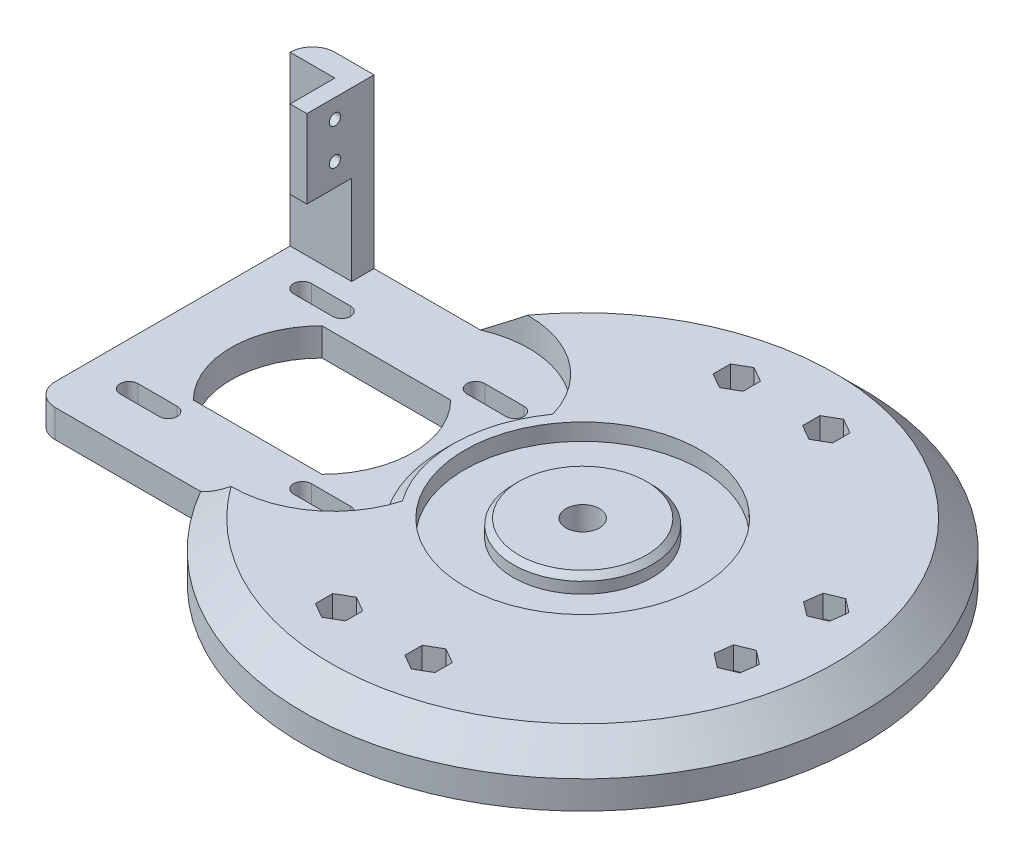
SolidWorks part; units mm, degrees
ref_plane "Front Plane" through (0, 0, 0) normal (0, 0, 1) x (1, 0, 0)
ref_plane "Top Plane" through (0, 0, 0) normal (0, 1, 0) x (1, 0, 0)
ref_plane "Right Plane" through (0, 0, 0) normal (1, 0, 0) x (0, 0, -1)
sketch "Sketch1" plane through (0, 0, 0) normal (0, 1, 0) x (1, 0, 0)
  line L0 (-43.3013, 25) -> (-73.3013, 25)
  line L2 (-73.3013, 25) -> (-73.3013, -25)
  line L3 (-43.3013, -25) -> (-73.3013, -25)
  line L4 (-50, 0) -> (-73.3013, -25) construction
  line L5 (-73.3013, 25) -> (-50, 0) construction
  line L6 (0, 0) -> (-50, 0) construction
  line L7 (-50, 0) -> (-73.3013, 0) construction
  circle A0 centre (0, 0) radius 50
  point P4 (-50, 0)
  dimension "D1" = 100
  dimension "D2" = 50
  dimension "D3" = 30
extrude "Boss-Extrude1" add sketch "Sketch1" along normal blind 5 contours A0 L0 L2 L3 | A0
sketch "Sketch2" plane through (0, 5, 0) normal (0, 1, 0) x (1, 0, 0)
  circle A0 centre (0, 0) radius 12.4
  circle A1 centre (0, 0) radius 9.4
  circle A2 centre (0, 0) radius 21.1
  circle A3 centre (0, 0) radius 25.1
  dimension "D1" = 24.8
  dimension "D2" = 3
  dimension "D3" = 42.2
  dimension "D4" = 4
extrude "Boss-Extrude2" add sketch "Sketch2" along normal blind 5 contours A3 A2 | A0 A1
chamfer "Chamfer1" distance 1 angle 45 1 edges at (0, 10, 12.4)
sketch "Sketch3" plane through (0, 5, 0) normal (0, 1, 0) x (1, 0, 0)
  circle A0 centre (0, 0) radius 9.4
extrude "Cut-Extrude1" cut sketch "Sketch3" against normal blind 5
sketch "Sketch4" plane through (0, 5, 0) normal (0, 1, 0) x (1, 0, 0)
  line L0 (-31.1, 0) -> (-62.1, 0) construction
  line L2 (-65.6, 15.5) -> (-58.6, 15.5) construction
  line L3 (-65.6, 17.1) -> (-58.6, 17.1)
  line L4 (-65.6, 13.9) -> (-58.6, 13.9)
  line L5 (-34.6, 15.5) -> (-27.6, 15.5) construction
  line L6 (-34.6, 17.1) -> (-27.6, 17.1)
  line L7 (-34.6, 13.9) -> (-27.6, 13.9)
  line L8 (-43.3013, 25) -> (-73.3013, 25) construction
  line L9 (-34.6, -15.5) -> (-27.6, -15.5) construction
  line L10 (-34.6, -17.1) -> (-27.6, -17.1)
  line L11 (-34.6, -13.9) -> (-27.6, -13.9)
  line L12 (-65.6, -15.5) -> (-58.6, -15.5) construction
  line L13 (-65.6, -17.1) -> (-58.6, -17.1)
  line L14 (-65.6, -13.9) -> (-58.6, -13.9)
  line L15 (-31.1, 15.5) -> (-31.1, -15.5) construction
  line L16 (-31.1, -15.5) -> (-62.1, -15.5) construction
  line L17 (-62.1, -15.5) -> (-62.1, 15.5) construction
  line L18 (-62.1, 15.5) -> (-31.1, 15.5) construction
  line L19 (-25.1, 0) -> (-31.1, 0) construction
  line L20 (-58.1, 11.5) -> (-35.1, 11.5)
  line L21 (-58.1, -11.5) -> (-35.1, -11.5)
  arc A2 (-65.6, 17.1) -> (-65.6, 13.9) centre (-65.6, 15.5) ccw
  arc A3 (-58.6, 13.9) -> (-58.6, 17.1) centre (-58.6, 15.5) ccw
  arc A4 (-34.6, 17.1) -> (-34.6, 13.9) centre (-34.6, 15.5) ccw
  arc A5 (-27.6, 13.9) -> (-27.6, 17.1) centre (-27.6, 15.5) ccw
  arc A6 (-34.6, -17.1) -> (-34.6, -13.9) centre (-34.6, -15.5) cw
  arc A7 (-27.6, -13.9) -> (-27.6, -17.1) centre (-27.6, -15.5) cw
  arc A8 (-65.6, -17.1) -> (-65.6, -13.9) centre (-65.6, -15.5) cw
  arc A9 (-58.6, -13.9) -> (-58.6, -17.1) centre (-58.6, -15.5) cw
  circle A10 centre (0, 0) radius 25.1 construction
  circle A11 centre (0, 0) radius 25.1 construction
  arc A13 (-58.1, 11.5) -> (-58.1, -11.5) centre (-46.6, 0) ccw
  arc A14 (-35.1, 11.5) -> (-35.1, -11.5) centre (-46.6, 0) cw
  point P10 (-62.1, 15.5)
  point P17 (-31.1, 15.5)
  point P26 (-31.1, -15.5)
  point P33 (-62.1, -15.5)
  point P46 (-46.6, 11.5)
  dimension "D3" = 4
  dimension "D1" = 7
  dimension "D2" = 3.2
  dimension "15.5" = 15.5
  dimension "D4" = 31
  dimension "D5" = 6
extrude "Cut-Extrude2" cut sketch "Sketch4" against normal blind 5
sketch "Sketch5" plane through (0, 5, 0) normal (0, 1, 0) x (1, 0, 0)
  line L1 (0, 0) -> (-6.0888, 0) construction
  circle A0 centre (0, 0) radius 25.1 construction
  arc A1 (-43.3013, -25) -> (-43.3013, 25) centre (0, 0) ccw
  arc A2 (-19.5937, -15.6875) -> (-19.5937, 15.6875) centre (0, 0) ccw
  arc A3 (-43.3013, -25) -> (-19.5937, -15.6875) centre (-36.1037, -8.49) ccw
  arc A4 (-43.3013, 25) -> (-19.5937, 15.6875) centre (-36.1037, 8.49) cw
extrude "Boss-Extrude3" add sketch "Sketch5" along normal blind 5
sketch "Sketch6" plane through (0, 10, 0) normal (0, 1, 0) x (1, 0, 0)
  line L0 (0, 0) -> (8.3145, 0) construction
  line L1 (0, -21.1) -> (0, -50) construction
  line L2 (-8, -35.55) -> (8, -35.55) construction
  line L3 (21.1, 0) -> (50, 0) construction
  line L4 (35.55, 8) -> (35.55, -8) construction
  circle A0 centre (0, 0) radius 21.1 construction
  circle A1 centre (0, 0) radius 21.1 construction
  arc A2 (-43.3013, -25) -> (-43.3013, 25) centre (0, 0) ccw construction
  circle A3 centre (8, -35.55) radius 1.5
  circle A4 centre (-8, -35.55) radius 1.5
  circle A5 centre (8, 35.55) radius 1.5
  circle A6 centre (-8, 35.55) radius 1.5
  circle A7 centre (35.55, -8) radius 1.5
  circle A8 centre (35.55, 8) radius 1.5
  point P28 (0, -35.55)
  point P33 (35.55, 0)
  dimension "D1" = 3
  dimension "D2" = 8
  dimension "D3" = 16
extrude "Cut-Extrude3" cut sketch "Sketch6" against normal blind 10
sketch "Sketch7" plane through (0, 10, 0) normal (0, 1, 0) x (1, 0, 0)
  line L0 (0, 0) -> (5.3153, 0) construction
  line L1 (-8, -38.65) -> (-5.3153, -37.1)
  line L2 (-5.3153, -37.1) -> (-5.3153, -34)
  line L3 (-5.3153, -34) -> (-8, -32.45)
  line L4 (-8, -32.45) -> (-10.6847, -34)
  line L5 (-10.6847, -34) -> (-10.6847, -37.1)
  line L6 (-10.6847, -37.1) -> (-8, -38.65)
  line L7 (8, -38.65) -> (10.6847, -37.1)
  line L8 (10.6847, -37.1) -> (10.6847, -34)
  line L9 (10.6847, -34) -> (8, -32.45)
  line L10 (8, -32.45) -> (5.3153, -34)
  line L11 (5.3153, -34) -> (5.3153, -37.1)
  line L12 (5.3153, -37.1) -> (8, -38.65)
  line L13 (5.3153, 37.1) -> (8, 38.65)
  line L14 (5.3153, 34) -> (5.3153, 37.1)
  line L15 (8, 32.45) -> (5.3153, 34)
  line L16 (10.6847, 34) -> (8, 32.45)
  line L17 (10.6847, 37.1) -> (10.6847, 34)
  line L18 (8, 38.65) -> (10.6847, 37.1)
  line L19 (-10.6847, 37.1) -> (-8, 38.65)
  line L20 (-10.6847, 34) -> (-10.6847, 37.1)
  line L21 (-8, 32.45) -> (-10.6847, 34)
  line L22 (-5.3153, 34) -> (-8, 32.45)
  line L23 (-5.3153, 37.1) -> (-5.3153, 34)
  line L24 (-8, 38.65) -> (-5.3153, 37.1)
  line L26 (32.6851, 6.8158) -> (35.1431, 4.9268)
  line L27 (35.1431, 4.9268) -> (38.008, 6.111)
  line L28 (38.008, 6.111) -> (38.4149, 9.1842)
  line L29 (38.4149, 9.1842) -> (35.9569, 11.0732)
  line L30 (35.9569, 11.0732) -> (33.092, 9.889)
  line L31 (33.092, 9.889) -> (32.6851, 6.8158)
  line L32 (32.6837, -9.1807) -> (35.1393, -11.0727)
  line L33 (35.1393, -11.0727) -> (38.0057, -9.892)
  line L34 (38.0057, -9.892) -> (38.4163, -6.8193)
  line L35 (38.4163, -6.8193) -> (35.9607, -4.9273)
  line L36 (35.9607, -4.9273) -> (33.0943, -6.108)
  line L37 (33.0943, -6.108) -> (32.6837, -9.1807)
  circle A0 centre (-8, -35.55) radius 2.6847 construction
  circle A1 centre (8, -35.55) radius 2.6847 construction
  circle A2 centre (35.55, 8) radius 2.6847 construction
  circle A3 centre (35.55, -8) radius 2.6847 construction
  dimension "D1" = 6.2
  dimension "D2" = 6.2
  dimension "D3" = 6.2
extrude "Cut-Extrude4" cut sketch "Sketch7" against normal blind 4
chamfer "Chamfer4" distance 2 angle 45 1 edges at (-25.1, 10, 0)
sketch "Sketch8" plane through (0, 5, 0) normal (0, 1, 0) x (1, 0, 0)
  line L0 (-67.2, -15.5) -> (-67.2, 15.5) construction
  line L2 (-26, 15.5) -> (-26, -15.5) construction
  line L3 (-26, 0) -> (-67.2, 0) construction
  line L5 (-46.6, 0) -> (-46.6, 3.8786) construction
  line L6 (-62.1, 11.5) -> (-39.1, 11.5)
  line L8 (-62.1, -11.5) -> (-39.1, -11.5)
  arc A1 (-65.6, -13.9) -> (-65.6, -17.1) centre (-65.6, -15.5) ccw construction
  arc A2 (-65.6, 17.1) -> (-65.6, 13.9) centre (-65.6, 15.5) ccw construction
  arc A3 (-27.6, 13.9) -> (-27.6, 17.1) centre (-27.6, 15.5) ccw construction
  arc A4 (-27.6, -17.1) -> (-27.6, -13.9) centre (-27.6, -15.5) ccw construction
  arc A10 (-62.1, 11.5) -> (-62.1, -11.5) centre (-50.6, 0) ccw
  arc A11 (-39.1, 11.5) -> (-39.1, -11.5) centre (-50.6, 0) cw
  point P22 (-50.6, 11.5)
sketch "Sketch10" plane through (0, 5, 0) normal (0, 1, 0) x (1, 0, 0)
  circle A0 centre (0, 0) radius 21.6386
  circle A1 centre (0, 0) radius 12.4
extrude "Boss-Extrude4" add sketch "Sketch10" along normal blind 2
chamfer "Chamfer5" distance 5 angle 45 1 edges at (50, 10, 0)
sketch "Sketch14" plane through (0, 0, 0) normal (0, -1, 0) x (1, 0, 0)
  circle A0 centre (0, 0) radius 9.4
  circle A1 centre (0, 0) radius 3
  dimension "D1" = 18.8
  dimension "D2" = 6
extrude "Boss-Extrude6" add sketch "Sketch14" along normal up to surface (10 mm away) from surface at -10 up to face at (35.55, 0, 9.5) starting at face at (0, 10, 11.4)
sketch "Sketch16" plane through (0, 0, 0) normal (0, -1, 0) x (1, 0, 0)
  circle A0 centre (0, 0) radius 9.4
  dimension "D1" = 18.8
extrude "Cut-Extrude8" cut sketch "Sketch16" against normal blind 4
fillet "Fillet3" radius 4 2 edges at (-73.3013, 2.5, -25) (-73.3013, 2.5, 25)
sketch "Sketch17" plane through (0, 5, 0) normal (0, 1, 0) x (1, 0, 0)
  line L5 (-73.3013, 21) -> (-73.3013, -21) construction
  line L6 (-73.3013, 0) -> (-64.3362, 0) construction
  line L8 (-65.3013, 25) -> (-65.3013, 21)
  line L9 (-69.3013, 25) -> (-65.3013, 25)
  line L11 (-65.3013, 21) -> (-73.3013, 21)
  arc A0 (-73.3013, 21) -> (-69.3013, 25) centre (-69.3013, 21) cw
  dimension "D1" = 8
extrude "Boss-Extrude7" add sketch "Sketch17" along normal blind 30
sketch "Sketch19" plane through (0, 0, -25) normal (0, 0, -1) x (-1, 0, 0)
sketch "Sketch22" plane through (-65.3013, 0, 0) normal (1, 0, 0) x (0, 0, -1)
  line L0 (25, 35) -> (13, 35)
  line L1 (13, 35) -> (13, 21)
  line L2 (13, 21) -> (25, 21)
  line L3 (25, 35) -> (25, 5) construction
  line L4 (25, 21) -> (25, 35)
  dimension "D1" = 14
  dimension "D2" = 12
extrude "Boss-Extrude10" add sketch "Sketch22" along normal blind 3
sketch "Sketch23" plane through (-65.3013, 0, 0) normal (-1, 0, 0) x (0, 0, 1)
  line L0 (-21, 35) -> (-13, 35) construction
  line L1 (-13, 35) -> (-13, 21) construction
  circle A0 centre (-18, 31.6) radius 1
  circle A1 centre (-18, 25.09) radius 1
  dimension "D1" = 2
  dimension "D2" = 6.51
  dimension "D3" = 3.4
  dimension "D4" = 5
extrude "Cut-Extrude11" cut sketch "Sketch23" against normal blind 3
sketch "Sketch24" plane through (0, 0, -25) normal (0, 0, -1) x (-1, 0, 0)
  line L0 (62.3013, 21) -> (62.3013, 5)
  line L1 (43.3013, 5) -> (65.3013, 5) construction
  line L2 (62.3013, 5) -> (65.3013, 5)
  line L3 (65.3013, 5) -> (65.3013, 21)
  line L4 (65.3013, 21) -> (62.3013, 21)
extrude "Boss-Extrude11" add sketch "Sketch24" against normal up to vertex (4 mm away) up to point (-65.3013, 21, -21)
